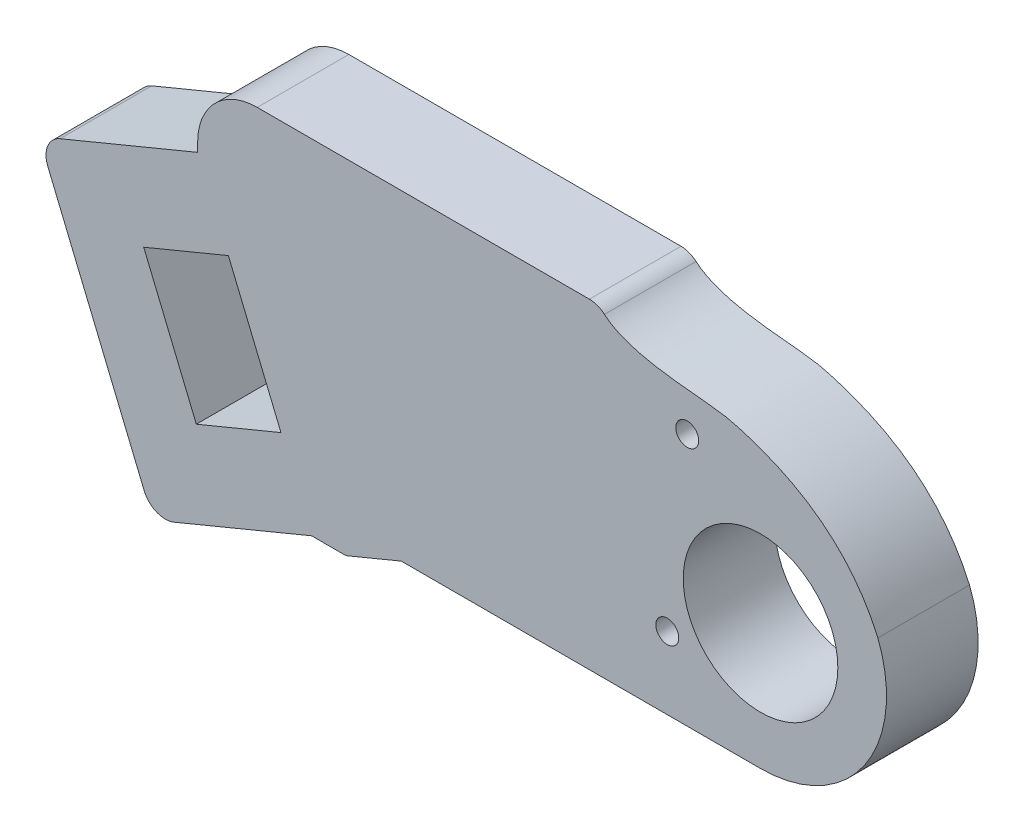
SolidWorks part; units mm, degrees
ref_plane "Piano frontale" through (0, 0, 0) normal (0, 0, 1) x (1, 0, 0)
ref_plane "Piano superiore" through (0, 0, 0) normal (0, 1, 0) x (1, 0, 0)
ref_plane "Piano destro" through (0, 0, 0) normal (1, 0, 0) x (0, 0, -1)
sketch "Schizzo1" plane through (0, 0, 0) normal (0, 0, 1) x (1, 0, 0)
  line L0 (-21.9709, 8.5104) -> (-7.4709, 8.5104)
  line L2 (0, -5.5) -> (-15.6818, -5.5)
  line L3 (-15.6818, -5.5) -> (-18.096, -6.5)
  line L4 (-18.096, -6.5) -> (-19.596, -6.5)
  line L5 (-19.596, -6.5) -> (-25.6012, -8.9874)
  line L6 (-26.9078, -8.4462) -> (-31.1173, 1.7164)
  line L7 (-30.5761, 3.023) -> (-24.5709, 5.5104)
  line L8 (-24.5709, 5.5104) -> (-24.5709, 5.9104)
  line L9 (-26.927, 0.7461) -> (-23.2315, 2.2769)
  line L14 (-23.2315, 2.2769) -> (-20.9354, -3.2664)
  line L15 (-20.9354, -3.2664) -> (-24.6309, -4.7972)
  line L16 (-24.6309, -4.7972) -> (-26.927, 0.7461)
  line L17 (-19.596, -6.5) -> (-24.5709, 5.5104)
  circle A1 centre (0, 0) radius 3.375
  circle A2 centre (0, 0) radius 5.5
  arc A3 (-21.9709, 8.5104) -> (-24.5709, 5.9104) centre (-21.9709, 5.9104) ccw
  arc A4 (-25.6012, -8.9874) -> (-26.9078, -8.4462) centre (-25.9839, -8.0636) cw
  arc A5 (-30.5761, 3.023) -> (-31.1173, 1.7164) centre (-30.1934, 2.0991) ccw
  arc A6 (-7.4709, 8.5104) -> (-6.8133, 8.2638) centre (-7.4709, 7.5104) cw
  spline S0 degree 3 poles (-6.8133, 8.2638) (-5.6849, 7.2787) (-2.242, 7.2615) (0.0386, 6.6388) (3.6537, 5.3641) (5.1235, 2) knots 0.028629 0.028629 0.028629 0.028629 0.40264 0.499777 1 1 1 1
  point P34 (-24.5709, 8.5104)
  point P46 (-31.5, 2.6403)
  dimension "D9" = 6.75
  dimension "D10" = 11
  dimension "D13" = 2.6
  dimension "D14" = 1
  dimension "D15" = 1
  dimension "D19" = 7
  dimension "D1" = 4
  dimension "D2" = 6
  dimension "D3" = 3.5
  dimension "D4" = 3.5
  dimension "D5" = 3
  dimension "D6" = 3.5
  dimension "D7" = 1.5
  dimension "D8" = 1
  dimension "D11" = 157.5
  dimension "D12" = 31.5
  dimension "D16" = 14.5
  dimension "D17" = 5.5
  dimension "D18" = 2
extrude "Estrusione-Estrusione1" add sketch "Schizzo1" along normal blind 4 contours S0 A6 L0 A3 L8 L17 L14 L4 L3 L2 A2 | S0 A2 A1 | L7 A5 L6 A4 L5 L17 L15 L16 L9
sketch "Schizzo2" plane through (0, 0, 4) normal (0, 0, 1) x (1, 0, 0)
  line L0 (-3.2, 5.5426) -> (0, 0) construction
  line L1 (0, 0) -> (-4.0703, -2.35) construction
  circle A0 centre (-3.2, 5.5426) radius 0.5
  circle A1 centre (-4.0703, -2.35) radius 0.5
  dimension "D1" = 1
  dimension "D2" = 1
  dimension "D3" = 6.4
  dimension "D5" = 3.2
  dimension "D4" = 4.7
extrude "Taglio-Estrusione1" cut sketch "Schizzo2" against normal through all
